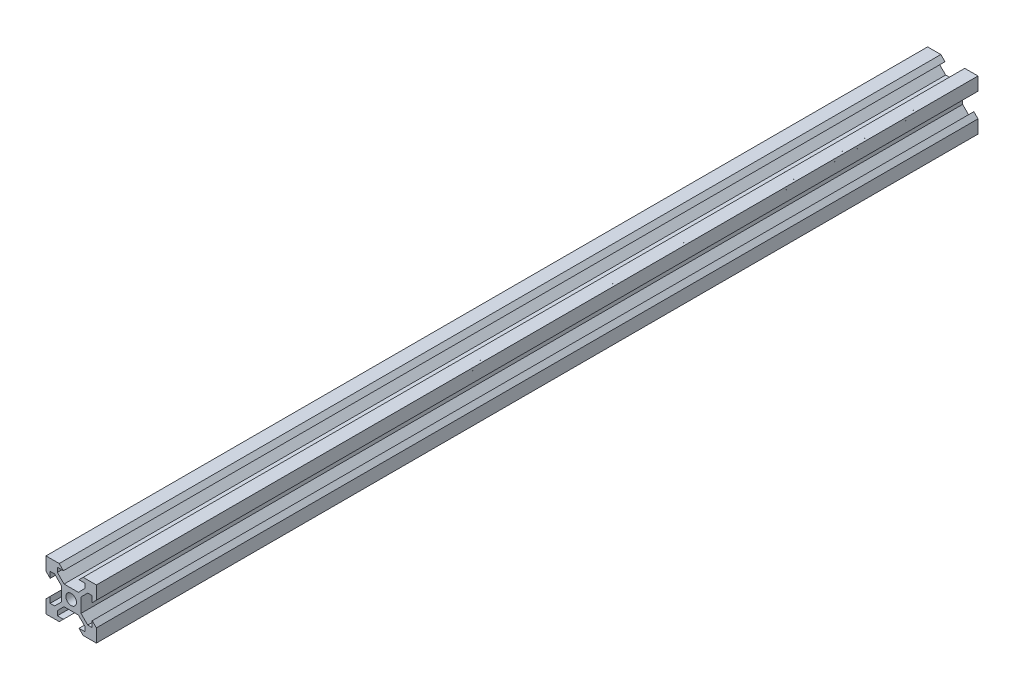
SolidWorks part; units mm, degrees
material "6061-T6 (SS)"
ref_plane "Front Plane" through (0, 0, 0) normal (0, 0, 1) x (1, 0, 0)
ref_plane "Top Plane" through (0, 0, 0) normal (0, 1, 0) x (1, 0, 0)
ref_plane "Right Plane" through (0, 0, 0) normal (1, 0, 0) x (0, 0, -1)
sketch "Sketch1" plane through (0, 0, 0) normal (0, 0, 1) x (1, 0, 0)
  line L0 (2.8343, 3.894) -> (5.5, 6.5588)
  line L1 (2.8343, -3.894) -> (-2.8343, -3.894)
  line L2 (3.8948, -2.8332) -> (3.8948, 2.8332)
  line L3 (2.8343, 3.894) -> (-2.8343, 3.894)
  line L4 (-3.8948, -2.8332) -> (-3.8948, 2.8332)
  line L5 (3.8994, -3.9006) -> (-3.8994, 3.9006) construction
  line L6 (3.9006, 3.8994) -> (-3.9006, -3.8994) construction
  line L7 (10, 4.747) -> (10, 9.9986)
  line L8 (5.5, 6.5588) -> (5.5, 8.3491)
  line L9 (5.5, 8.3491) -> (3.1, 8.3491)
  line L10 (3.1, 8.3491) -> (4.75, 9.9986)
  line L11 (4.75, 9.9986) -> (10, 9.9986)
  line L12 (8.35, 3.0975) -> (10, 4.747)
  line L13 (8.3507, 5.4975) -> (8.35, 3.0975)
  line L14 (6.5605, 5.498) -> (8.3507, 5.4975)
  line L15 (3.8948, 2.8332) -> (6.5605, 5.498)
  line L16 (0, -55) -> (0, 55) construction
  line L17 (-3.8948, 2.8332) -> (-6.5605, 5.498)
  line L18 (-6.5605, 5.498) -> (-8.3507, 5.4975)
  line L19 (-8.3507, 5.4975) -> (-8.35, 3.0975)
  line L20 (-8.35, 3.0975) -> (-10, 4.747)
  line L21 (-4.75, 9.9986) -> (-10, 9.9986)
  line L22 (-3.1, 8.3491) -> (-4.75, 9.9986)
  line L23 (-5.5, 8.3491) -> (-3.1, 8.3491)
  line L24 (-5.5, 6.5588) -> (-5.5, 8.3491)
  line L25 (-10, 4.747) -> (-10, 9.9986)
  line L26 (-2.8343, 3.894) -> (-5.5, 6.5588)
  line L27 (55, 0) -> (-55, 0) construction
  line L28 (3.8948, -2.8332) -> (6.5605, -5.498)
  line L29 (2.8343, -3.894) -> (5.5, -6.5588)
  line L30 (-3.8948, -2.8332) -> (-6.5605, -5.498)
  line L31 (-2.8343, -3.894) -> (-5.5, -6.5588)
  line L32 (-8.3507, -5.4975) -> (-8.35, -3.0975)
  line L33 (-8.35, -3.0975) -> (-10, -4.747)
  line L34 (8.3507, -5.4975) -> (8.35, -3.0975)
  line L35 (8.35, -3.0975) -> (10, -4.747)
  line L36 (-10, -4.747) -> (-10, -9.9986)
  line L37 (-5.5, -6.5588) -> (-5.5, -8.3491)
  line L38 (-5.5, -8.3491) -> (-3.1, -8.3491)
  line L39 (-3.1, -8.3491) -> (-4.75, -9.9986)
  line L40 (-4.75, -9.9986) -> (-10, -9.9986)
  line L41 (-6.5605, -5.498) -> (-8.3507, -5.4975)
  line L42 (6.5605, -5.498) -> (8.3507, -5.4975)
  line L43 (4.75, -9.9986) -> (10, -9.9986)
  line L44 (3.1, -8.3491) -> (4.75, -9.9986)
  line L45 (5.5, -8.3491) -> (3.1, -8.3491)
  line L46 (5.5, -6.5588) -> (5.5, -8.3491)
  line L47 (10, -4.747) -> (10, -9.9986)
  circle A0 centre (0, 0) radius 2.1
  point P0 (0, 0)
  dimension "D6" = 4.2
  dimension "D1" = 7.8
  dimension "D2" = 20
  dimension "D3" = 11
  dimension "D4" = 9.5
  dimension "D5" = 6.2
  dimension "D7" = 1.5
extrude "Boss-Extrude1" add sketch "Sketch1" along normal blind 350
